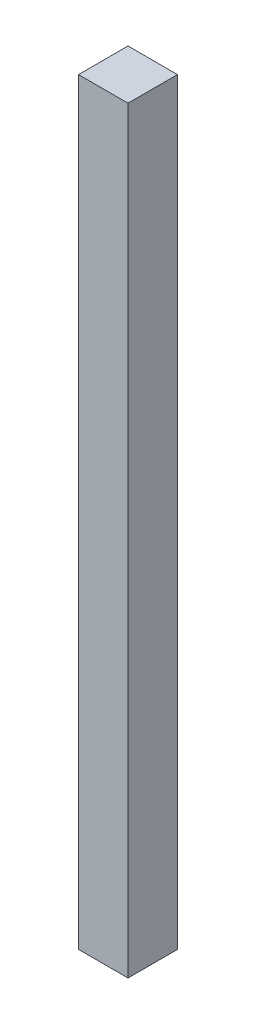
SolidWorks part; units mm, degrees
ref_plane "Front Plane" through (0, 0, 0) normal (0, 0, 1) x (1, 0, 0)
ref_plane "Top Plane" through (0, 0, 0) normal (0, 1, 0) x (1, 0, 0)
ref_plane "Right Plane" through (0, 0, 0) normal (1, 0, 0) x (0, 0, -1)
sketch "Sketch4" plane through (0, 0, 0) normal (0, 1, 0) x (1, 0, 0)
  line L1 (0, 0) -> (20, 0)
  line L2 (0, 0) -> (0, 20)
  line L3 (0, 20) -> (20, 20)
  line L4 (20, 0) -> (20, 20)
  dimension "D1" = 20
extrude "Boss-Extrude2" add sketch "Sketch4" along normal blind 306
